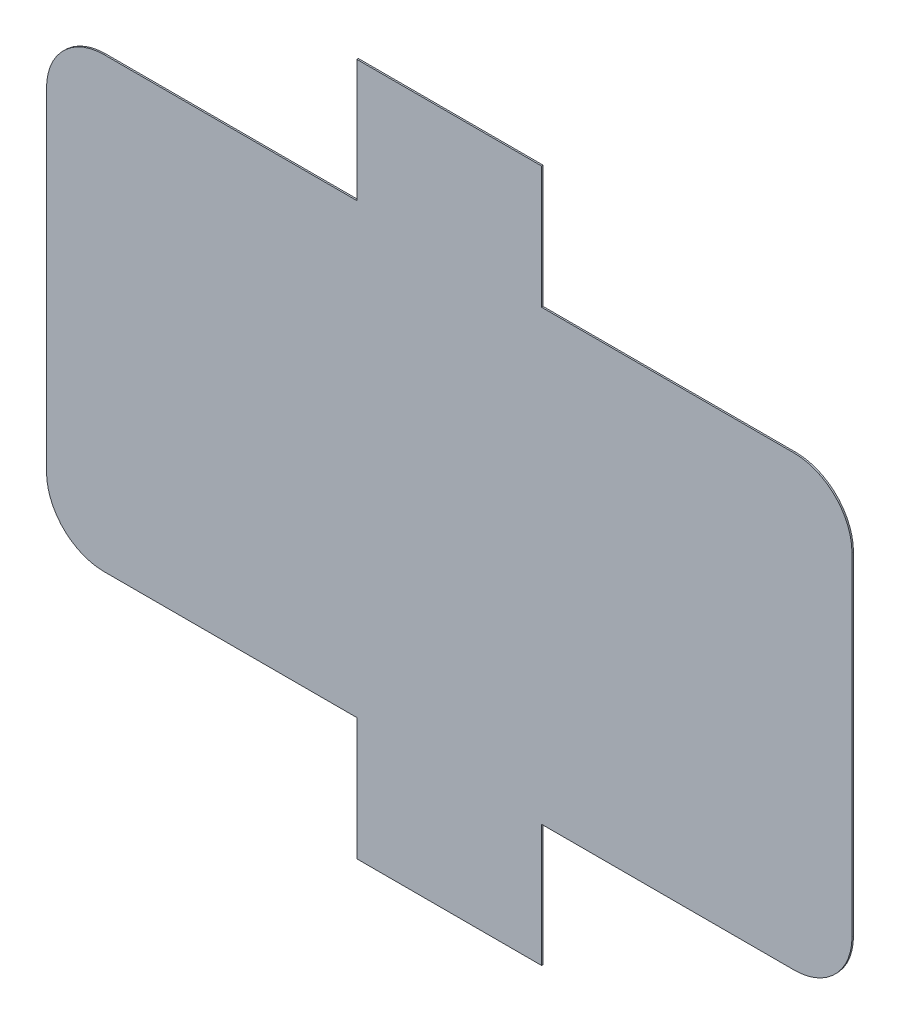
SolidWorks part; units mm, degrees
ref_plane "前基準面" through (0, 0, 0) normal (0, 0, 1) x (1, 0, 0)
ref_plane "上基準面" through (0, 0, 0) normal (0, 1, 0) x (1, 0, 0)
ref_plane "右基準面" through (0, 0, 0) normal (1, 0, 0) x (0, 0, -1)
sketch "草圖1" plane through (0, 0, 0) normal (0, 0, 1) x (1, 0, 0)
  line L1 (-38, 30) -> (38, 30)
  line L2 (-38, 30) -> (-38, -30)
  line L3 (-38, -30) -> (38, -30)
  line L4 (38, 30) -> (38, -30)
  line L5 (-38, 30) -> (38, -30) construction
  line L6 (-38, -30) -> (38, 30) construction
  point P0 (0, 0)
  dimension "D1" = 76
  dimension "D2" = 60
extrude "填料-伸長1" add sketch "草圖1" along normal blind 0.13
sketch "草圖2" plane through (0, 0, 0.13) normal (0, 0, 1) x (1, 0, 0)
  line L0 (0, 30) -> (0, -30) construction
  line L1 (-38, 30) -> (-8, 30)
  line L2 (-38, 30) -> (-38, 20)
  line L3 (-38, 20) -> (-8, 20)
  line L4 (-8, 30) -> (-8, 20)
  line L5 (38, 30) -> (-38, 30) construction
  line L6 (-38, -30) -> (38, -30) construction
  line L7 (-38, 0) -> (38, 0) construction
  line L8 (-38, 30) -> (-38, -30) construction
  line L9 (38, -30) -> (38, 30) construction
  line L10 (38, 20) -> (8, 20)
  line L11 (8, 30) -> (8, 20)
  line L12 (38, 30) -> (8, 30)
  line L13 (38, 30) -> (38, 20)
  line L14 (38, -30) -> (38, -20)
  line L15 (38, -30) -> (8, -30)
  line L16 (8, -30) -> (8, -20)
  line L17 (38, -20) -> (8, -20)
  line L18 (-38, -20) -> (-8, -20)
  line L19 (-8, -30) -> (-8, -20)
  line L20 (-38, -30) -> (-8, -30)
  line L21 (-38, -30) -> (-38, -20)
  dimension "D1" = 30
  dimension "D2" = 10
extrude "除料-伸長1" cut sketch "草圖2" against normal through all
sketch "草圖3" plane through (0, 0, 0.13) normal (0, 0, 1) x (1, 0, 0)
  line L0 (-38, 20) -> (-38, -20) construction
  line L1 (-8, 19.4) -> (-29.9, 19.4)
  line L2 (-34.9, 14.4) -> (-34.9, -14.4)
  line L3 (-29.9, -19.4) -> (-8, -19.4)
  line L4 (-38, 20) -> (-8, 20) construction
  line L5 (-8, -20) -> (-38, -20) construction
  line L6 (0, 30) -> (0, -30) construction
  line L7 (8, 30) -> (-8, 30) construction
  line L8 (-8, -30) -> (8, -30) construction
  line L9 (-8, 20) -> (-8, 19.4)
  line L10 (-8, 20) -> (-38, 20)
  line L11 (-38, 20) -> (-38, -20)
  line L12 (-38, -20) -> (-8, -20)
  line L13 (-8, -20) -> (-8, -19.4)
  line L14 (8, -20) -> (8, -19.4)
  line L15 (38, -20) -> (8, -20)
  line L16 (38, 20) -> (38, -20)
  line L17 (8, 20) -> (38, 20)
  line L18 (8, 20) -> (8, 19.4)
  line L19 (29.9, -19.4) -> (8, -19.4)
  line L20 (34.9, 14.4) -> (34.9, -14.4)
  line L21 (8, 19.4) -> (29.9, 19.4)
  arc A0 (-34.9, -14.4) -> (-29.9, -19.4) centre (-29.9, -14.4) ccw
  arc A1 (-29.9, 19.4) -> (-34.9, 14.4) centre (-29.9, 14.4) ccw
  arc A2 (29.9, 19.4) -> (34.9, 14.4) centre (29.9, 14.4) cw
  arc A3 (34.9, -14.4) -> (29.9, -19.4) centre (29.9, -14.4) cw
  point P29 (0, 0)
  dimension "D5" = 5
  dimension "D1" = 0.6
  dimension "D2" = 3.1
  dimension "D3" = 0.6
  dimension "D4" = 0.6
extrude "除料-伸長2" cut sketch "草圖3" against normal through all
